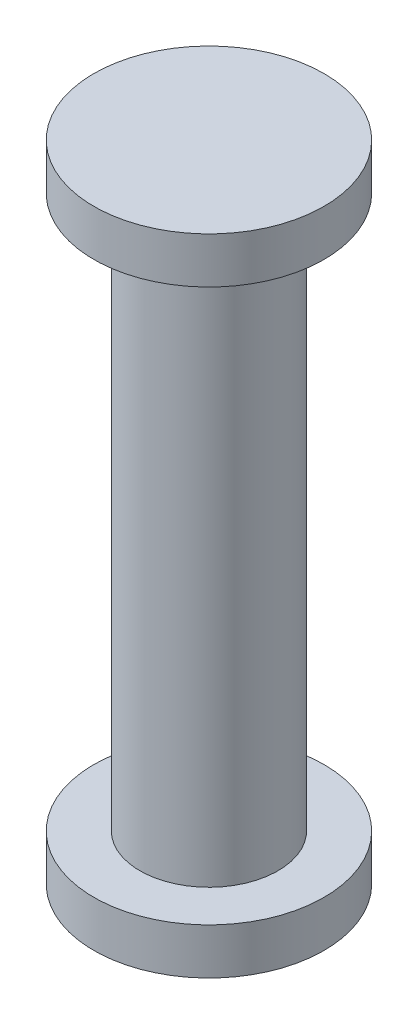
SolidWorks part; units mm, degrees
material "Alumina"
ref_plane "Front Plane" through (0, 0, 0) normal (0, 0, 1) x (1, 0, 0)
ref_plane "Top Plane" through (0, 0, 0) normal (0, 1, 0) x (1, 0, 0)
ref_plane "Right Plane" through (0, 0, 0) normal (1, 0, 0) x (0, 0, -1)
sketch "Sketch1" plane through (0, 0, 0) normal (0, 0, 1) x (1, 0, 0)
  line L0 (0, 0) -> (0, 14)
  line L3 (-1.5, 1) -> (-2.5, 1)
  line L4 (-2.5, 1) -> (-2.5, 0)
  line L5 (-2.5, 0) -> (0, 0)
  line L6 (0, 14) -> (-2.5, 14)
  line L7 (-2.5, 14) -> (-2.5, 13)
  line L8 (-2.5, 13) -> (-1.5, 13)
  line L9 (-1.5, 13) -> (-1.5, 1)
  dimension "D1" = 14
  dimension "D2" = 1
  dimension "D3" = 2.5
  dimension "D4" = 1.5
revolve "Revolve1" add sketch "Sketch1" angle 360 about L0
